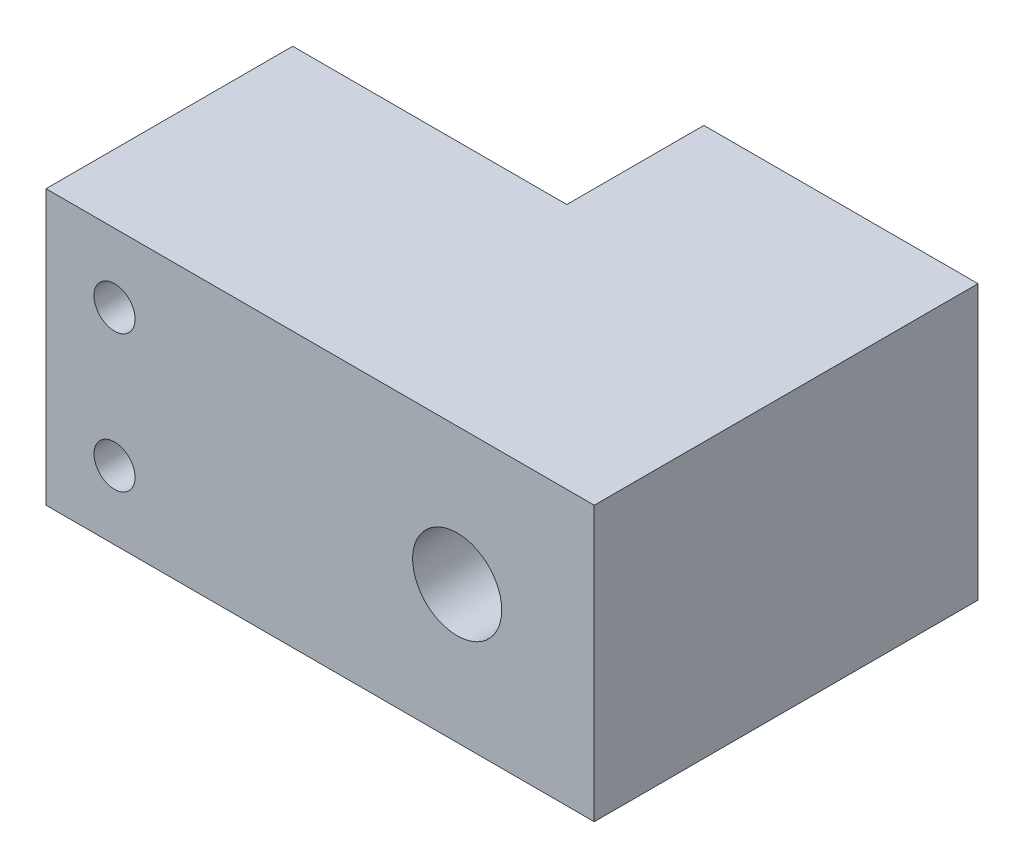
SolidWorks part; units mm, degrees
material "6061 Alloy"
ref_plane "Front Plane" through (0, 0, 0) normal (0, 0, 1) x (1, 0, 0)
ref_plane "Top Plane" through (0, 0, 0) normal (0, 1, 0) x (1, 0, 0)
ref_plane "Right Plane" through (0, 0, 0) normal (1, 0, 0) x (0, 0, -1)
sketch "Sketch1" plane through (0, 0, 0) normal (0, 0, 1) x (1, 0, 0)
  line L1 (0, 0) -> (40, 0)
  line L2 (0, 0) -> (0, 20)
  line L3 (0, 20) -> (40, 20)
  line L4 (40, 0) -> (40, 20)
  dimension "D1" = 20
  dimension "D2" = 40
extrude "Boss-Extrude1" add sketch "Sketch1" along normal blind 18
sketch "Sketch3" plane through (0, 0, 0) normal (0, 0, -1) x (-1, 0, 0)
  line L1 (-40, 0) -> (-40, 20) construction
  line L2 (-40, 0) -> (-20, 0)
  line L3 (-40, 0) -> (-40, 20)
  line L4 (-40, 20) -> (-20, 20)
  line L5 (-20, 0) -> (-20, 20)
  line L6 (-40, 20) -> (0, 20) construction
  line L7 (55, 0) -> (-55, 0) construction
  dimension "D1" = 20
extrude "Boss-Extrude2" add sketch "Sketch3" along normal blind 10
sketch "Sketch2" plane through (0, 0, 18) normal (0, 0, 1) x (1, 0, 0)
  line L0 (40, 20) -> (0, 20) construction
  line L1 (40, 0) -> (40, 20) construction
  line L2 (0, -9.9) -> (0, 9.9) construction
  circle A0 centre (30, 10) radius 3.25
  circle A1 centre (5, 15) radius 1.5
  circle A2 centre (5, 5) radius 1.5
  dimension "D1" = 6.5
  dimension "D2" = 10
  dimension "D3" = 10
  dimension "D4" = 10
  dimension "D5" = 5
  dimension "D6" = 5
  dimension "D7" = 3
extrude "Cut-Extrude1" cut sketch "Sketch2" against normal blind 65
